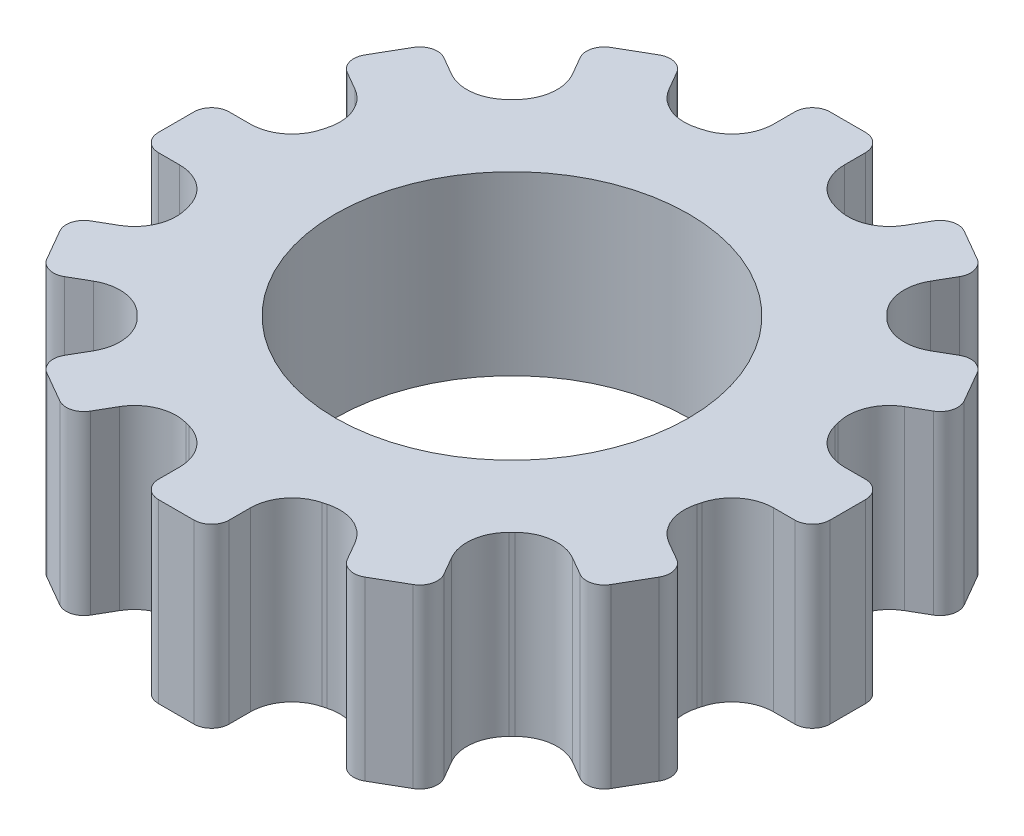
SolidWorks part; units mm, degrees
ref_plane "Front Plane" through (0, 0, 0) normal (0, 0, 1) x (1, 0, 0)
ref_plane "Top Plane" through (0, 0, 0) normal (0, 1, 0) x (1, 0, 0)
ref_plane "Right Plane" through (0, 0, 0) normal (1, 0, 0) x (0, 0, -1)
sketch "Sketch1" plane through (0, 0, 0) normal (0, 1, 0) x (1, 0, 0)
  line L0 (0, 0) -> (0, 9.525) construction
  line L7 (-1.27, 10.6703) -> (-1.27, 11.43)
  line L8 (-0.635, 12.065) -> (0.635, 12.065)
  line L9 (1.27, 11.43) -> (1.27, 10.6703)
  line L10 (4.2353, 9.8757) -> (4.6151, 10.5337)
  line L11 (5.4826, 10.7661) -> (6.5824, 10.1311)
  line L12 (6.8149, 9.2637) -> (6.435, 8.6057)
  line L13 (8.6057, 6.435) -> (9.2637, 6.8149)
  line L14 (10.1311, 6.5824) -> (10.7661, 5.4826)
  line L15 (10.5337, 4.6151) -> (9.8757, 4.2353)
  line L16 (10.6703, 1.27) -> (11.43, 1.27)
  line L17 (12.065, 0.635) -> (12.065, -0.635)
  line L18 (11.43, -1.27) -> (10.6703, -1.27)
  line L19 (9.8757, -4.2353) -> (10.5337, -4.6151)
  line L20 (10.7661, -5.4826) -> (10.1311, -6.5824)
  line L21 (9.2637, -6.8149) -> (8.6057, -6.435)
  line L22 (6.435, -8.6057) -> (6.8149, -9.2637)
  line L23 (6.5824, -10.1311) -> (5.4826, -10.7661)
  line L24 (4.6151, -10.5337) -> (4.2353, -9.8757)
  line L25 (1.27, -10.6703) -> (1.27, -11.43)
  line L26 (0.635, -12.065) -> (-0.635, -12.065)
  line L27 (-1.27, -11.43) -> (-1.27, -10.6703)
  line L28 (-4.2353, -9.8757) -> (-4.6151, -10.5337)
  line L29 (-5.4826, -10.7661) -> (-6.5824, -10.1311)
  line L30 (-6.8149, -9.2637) -> (-6.435, -8.6057)
  line L31 (-8.6057, -6.435) -> (-9.2637, -6.8149)
  line L32 (-10.1311, -6.5824) -> (-10.7661, -5.4826)
  line L33 (-10.5337, -4.6151) -> (-9.8757, -4.2353)
  line L34 (-10.6703, -1.27) -> (-11.43, -1.27)
  line L35 (-12.065, -0.635) -> (-12.065, 0.635)
  line L36 (-11.43, 1.27) -> (-10.6703, 1.27)
  line L37 (-9.8757, 4.2353) -> (-10.5337, 4.6151)
  line L38 (-10.7661, 5.4826) -> (-10.1311, 6.5824)
  line L39 (-9.2637, 6.8149) -> (-8.6057, 6.435)
  line L40 (-6.435, 8.6057) -> (-6.8149, 9.2637)
  line L41 (-6.5824, 10.1311) -> (-5.4826, 10.7661)
  line L42 (-4.6151, 10.5337) -> (-4.2353, 9.8757)
  line L43 (0, 0) -> (2.3922, 9.2197) construction
  line L44 (-2.3922, 9.2197) -> (-2.5381, 9.1806)
  line L45 (2.5381, 9.1806) -> (2.3922, 9.2197)
  line L46 (6.7884, 6.6816) -> (6.6816, 6.7884)
  line L47 (9.2197, 2.3922) -> (9.1806, 2.5381)
  line L48 (9.1806, -2.5381) -> (9.2197, -2.3922)
  line L49 (6.6816, -6.7884) -> (6.7884, -6.6816)
  line L50 (2.3922, -9.2197) -> (2.5381, -9.1806)
  line L51 (-2.5381, -9.1806) -> (-2.3922, -9.2197)
  line L52 (-6.7884, -6.6816) -> (-6.6816, -6.7884)
  line L53 (-9.2197, -2.3922) -> (-9.1806, -2.5381)
  line L54 (-9.1806, 2.5381) -> (-9.2197, 2.3922)
  line L55 (-6.6816, 6.7884) -> (-6.7884, 6.6816)
  line L56 (0, 0) -> (-2.5381, 9.1806) construction
  circle A0 centre (0, 0) radius 6.35
  circle A1 centre (0, 0) radius 9.525 construction
  arc A2 (-2.3922, 9.2197) -> (-1.27, 10.6703) centre (-2.7686, 10.6703) ccw
  arc A3 (0.635, 12.065) -> (1.27, 11.43) centre (0.635, 11.43) cw
  arc A4 (1.27, 10.6703) -> (2.3922, 9.2197) centre (2.7686, 10.6703) ccw
  arc A5 (-1.27, 11.43) -> (-0.635, 12.065) centre (-0.635, 11.43) cw
  arc A6 (2.5381, 9.1806) -> (4.2353, 9.8757) centre (2.9375, 10.625) ccw
  arc A7 (6.5824, 10.1311) -> (6.8149, 9.2637) centre (6.2649, 9.5812) cw
  arc A8 (6.435, 8.6057) -> (6.6816, 6.7884) centre (7.7328, 7.8564) ccw
  arc A9 (4.6151, 10.5337) -> (5.4826, 10.7661) centre (5.1651, 10.2162) cw
  arc A10 (6.7884, 6.6816) -> (8.6057, 6.435) centre (7.8564, 7.7328) ccw
  arc A11 (10.7661, 5.4826) -> (10.5337, 4.6151) centre (10.2162, 5.1651) cw
  arc A12 (9.8757, 4.2353) -> (9.1806, 2.5381) centre (10.625, 2.9375) ccw
  arc A13 (9.2637, 6.8149) -> (10.1311, 6.5824) centre (9.5812, 6.2649) cw
  arc A14 (9.2197, 2.3922) -> (10.6703, 1.27) centre (10.6703, 2.7686) ccw
  arc A15 (12.065, -0.635) -> (11.43, -1.27) centre (11.43, -0.635) cw
  arc A16 (10.6703, -1.27) -> (9.2197, -2.3922) centre (10.6703, -2.7686) ccw
  arc A17 (11.43, 1.27) -> (12.065, 0.635) centre (11.43, 0.635) cw
  arc A18 (9.1806, -2.5381) -> (9.8757, -4.2353) centre (10.625, -2.9375) ccw
  arc A19 (10.1311, -6.5824) -> (9.2637, -6.8149) centre (9.5812, -6.2649) cw
  arc A20 (8.6057, -6.435) -> (6.7884, -6.6816) centre (7.8564, -7.7328) ccw
  arc A21 (10.5337, -4.6151) -> (10.7661, -5.4826) centre (10.2162, -5.1651) cw
  arc A22 (6.6816, -6.7884) -> (6.435, -8.6057) centre (7.7328, -7.8564) ccw
  arc A23 (5.4826, -10.7661) -> (4.6151, -10.5337) centre (5.1651, -10.2162) cw
  arc A24 (4.2353, -9.8757) -> (2.5381, -9.1806) centre (2.9375, -10.625) ccw
  arc A25 (6.8149, -9.2637) -> (6.5824, -10.1311) centre (6.2649, -9.5812) cw
  arc A26 (2.3922, -9.2197) -> (1.27, -10.6703) centre (2.7686, -10.6703) ccw
  arc A27 (-0.635, -12.065) -> (-1.27, -11.43) centre (-0.635, -11.43) cw
  arc A28 (-1.27, -10.6703) -> (-2.3922, -9.2197) centre (-2.7686, -10.6703) ccw
  arc A29 (1.27, -11.43) -> (0.635, -12.065) centre (0.635, -11.43) cw
  arc A30 (-2.5381, -9.1806) -> (-4.2353, -9.8757) centre (-2.9375, -10.625) ccw
  arc A31 (-6.5824, -10.1311) -> (-6.8149, -9.2637) centre (-6.2649, -9.5812) cw
  arc A32 (-6.435, -8.6057) -> (-6.6816, -6.7884) centre (-7.7328, -7.8564) ccw
  arc A33 (-4.6151, -10.5337) -> (-5.4826, -10.7661) centre (-5.1651, -10.2162) cw
  arc A34 (-6.7884, -6.6816) -> (-8.6057, -6.435) centre (-7.8564, -7.7328) ccw
  arc A35 (-10.7661, -5.4826) -> (-10.5337, -4.6151) centre (-10.2162, -5.1651) cw
  arc A36 (-9.8757, -4.2353) -> (-9.1806, -2.5381) centre (-10.625, -2.9375) ccw
  arc A37 (-9.2637, -6.8149) -> (-10.1311, -6.5824) centre (-9.5812, -6.2649) cw
  arc A38 (-9.2197, -2.3922) -> (-10.6703, -1.27) centre (-10.6703, -2.7686) ccw
  arc A39 (-12.065, 0.635) -> (-11.43, 1.27) centre (-11.43, 0.635) cw
  arc A40 (-10.6703, 1.27) -> (-9.2197, 2.3922) centre (-10.6703, 2.7686) ccw
  arc A41 (-11.43, -1.27) -> (-12.065, -0.635) centre (-11.43, -0.635) cw
  arc A42 (-9.1806, 2.5381) -> (-9.8757, 4.2353) centre (-10.625, 2.9375) ccw
  arc A43 (-10.1311, 6.5824) -> (-9.2637, 6.8149) centre (-9.5812, 6.2649) cw
  arc A44 (-8.6057, 6.435) -> (-6.7884, 6.6816) centre (-7.8564, 7.7328) ccw
  arc A45 (-10.5337, 4.6151) -> (-10.7661, 5.4826) centre (-10.2162, 5.1651) cw
  arc A46 (-6.6816, 6.7884) -> (-6.435, 8.6057) centre (-7.7328, 7.8564) ccw
  arc A47 (-5.4826, 10.7661) -> (-4.6151, 10.5337) centre (-5.1651, 10.2162) cw
  arc A48 (-4.2353, 9.8757) -> (-2.5381, 9.1806) centre (-2.9375, 10.625) ccw
  arc A49 (-6.8149, 9.2637) -> (-6.5824, 10.1311) centre (-6.2649, 9.5812) cw
  point P1 (0, 12.065)
  point P26 (6.0325, 10.4486)
  point P39 (10.4486, 6.0325)
  point P52 (12.065, 0)
  point P65 (10.4486, -6.0325)
  point P78 (6.0325, -10.4486)
  point P91 (0, -12.065)
  point P104 (-6.0325, -10.4486)
  point P117 (-10.4486, -6.0325)
  point P130 (-12.065, 0)
  point P143 (-10.4486, 6.0325)
  point P156 (-6.0325, 10.4486)
  dimension "D2" = 19.05
  dimension "D3" = 1.4986
  dimension "D6" = 0.635
  dimension "D11" = 12.7
  dimension "D4" = 2.54
  dimension "D5" = 2.54
  dimension "D9" = 12
  dimension "D7" = 12
extrude "Boss-Extrude1" add sketch "Sketch1" along normal blind 6.35 contours A49 L40 A46 L55 A44 L39 A43 L38 A45 L37 A42 L54 A40 L36 A39 L35 A41 L34 A38 L53 A36 L33 A35 L32 A37 L31 A34 L52 A32 L30 A31 L29 A33 L28 A30 L51 A28 L27 A27 L26 A29 L25 A26 L50 A24 L24 A23 L23 A25 L22 A22
